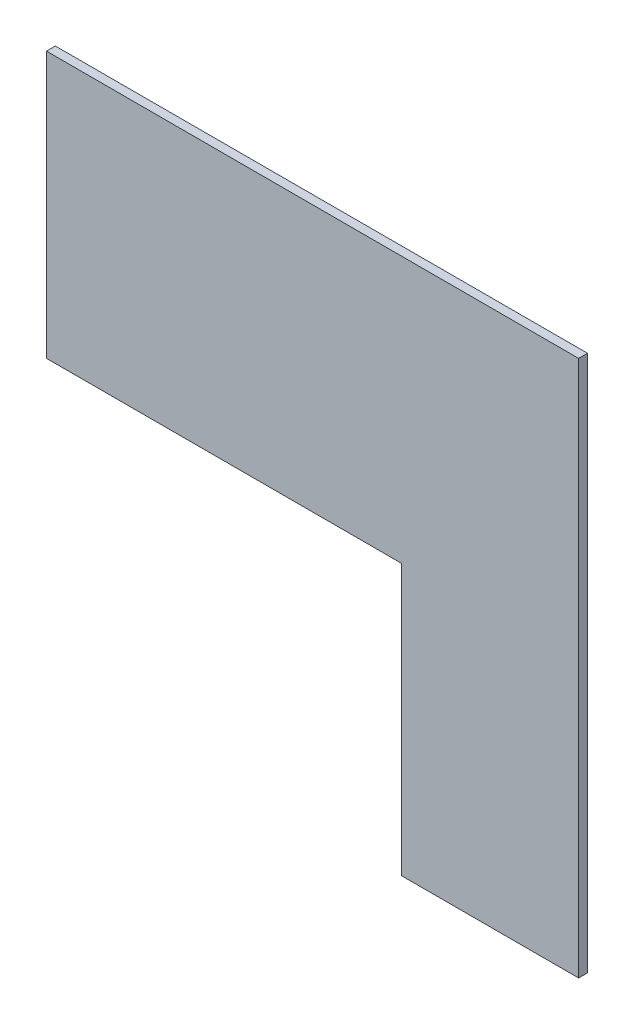
SolidWorks part; units mm, degrees
ref_plane "Plan de face" through (0, 0, 0) normal (0, 0, 1) x (1, 0, 0)
ref_plane "Plan de dessus" through (0, 0, 0) normal (0, 1, 0) x (1, 0, 0)
ref_plane "Plan de droite" through (0, 0, 0) normal (1, 0, 0) x (0, 0, -1)
sketch "Esquisse1" plane through (0, 0, 0) normal (0, 0, 1) x (1, 0, 0)
  line L0 (0, 0) -> (0, 600)
  line L1 (0, 600) -> (1200, 600)
  line L2 (1200, 600) -> (1200, -610)
  line L3 (1200, -610) -> (800, -610)
  line L4 (800, -610) -> (800, 0)
  line L5 (800, 0) -> (0, 0)
  dimension "D1" = 400
  dimension "D2" = 600
  dimension "D3" = 1200
  dimension "D4" = 610
extrude "Boss.-Extru.1" add sketch "Esquisse1" along normal blind 20
